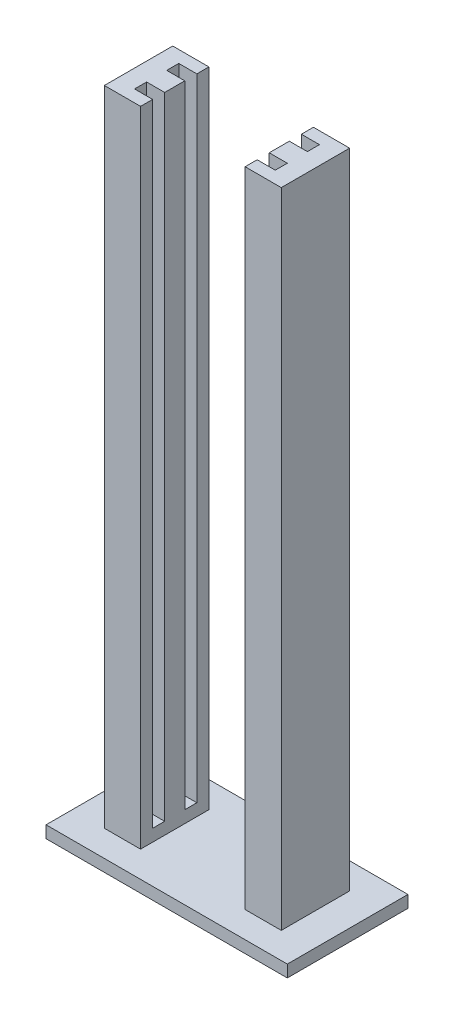
SolidWorks part; units mm, degrees
ref_plane "Front Plane" through (0, 0, 0) normal (0, 0, 1) x (1, 0, 0)
ref_plane "Top Plane" through (0, 0, 0) normal (0, 1, 0) x (1, 0, 0)
ref_plane "Right Plane" through (0, 0, 0) normal (1, 0, 0) x (0, 0, -1)
sketch "Sketch1" plane through (0, 0, 0) normal (0, 1, 0) x (1, 0, 0)
  line L1 (30, 15) -> (-30, 15)
  line L2 (30, 15) -> (30, -15)
  line L3 (30, -15) -> (-30, -15)
  line L4 (-30, 15) -> (-30, -15)
  line L5 (30, 15) -> (-30, -15) construction
  line L6 (30, -15) -> (-30, 15) construction
  point P0 (0, 0)
  dimension "D1" = 30
  dimension "D2" = 60
extrude "Boss-Extrude1" add sketch "Sketch1" along normal blind 3
sketch "Sketch2" plane through (0, 3, 0) normal (0, 1, 0) x (1, 0, 0)
  line L0 (0, 0) -> (-30, 0) construction
  line L1 (-30, 15) -> (-30, -15) construction
  line L2 (0, 0) -> (0, 15) construction
  line L3 (30, 15) -> (-30, 15) construction
  line L4 (13, -8.5) -> (22, -8.5)
  line L5 (-13, 8.5) -> (-22, 8.5)
  line L6 (-13, 8.5) -> (-13, -8.5)
  line L7 (-13, -8.5) -> (-22, -8.5)
  line L8 (-22, 8.5) -> (-22, -8.5)
  line L9 (-13, 8.5) -> (-22, -8.5) construction
  line L10 (-13, -8.5) -> (-22, 8.5) construction
  line L11 (22, 8.5) -> (22, -8.5)
  line L12 (13, 8.5) -> (22, 8.5)
  line L13 (13, 8.5) -> (13, -8.5)
  point P5 (-17.5, 0)
  dimension "D1" = 9
  dimension "D2" = 17
  dimension "D3" = 13
extrude "Boss-Extrude2" add sketch "Sketch2" along normal blind 160
sketch "Sketch3" plane through (0, 163, 0) normal (0, 1, 0) x (1, 0, 0)
  line L0 (-13, -8.5) -> (-13, 8.5) construction
  line L1 (-13, 5.5) -> (-17.5, 5.5)
  line L2 (-13, 5.5) -> (-13, 2.5)
  line L3 (-13, 2.5) -> (-17.5, 2.5)
  line L4 (-17.5, 5.5) -> (-17.5, 2.5)
  line L5 (-13, -8.5) -> (-13, 8.5) construction
  line L6 (-13, -2.5) -> (-17.5, -2.5)
  line L7 (-13, -2.5) -> (-13, -5.5)
  line L8 (-13, -5.5) -> (-17.5, -5.5)
  line L9 (-17.5, -2.5) -> (-17.5, -5.5)
  line L10 (0, 0) -> (0, 9.8393) construction
  line L11 (13, -5.5) -> (17.5, -5.5)
  line L12 (17.5, -2.5) -> (17.5, -5.5)
  line L13 (13, -2.5) -> (17.5, -2.5)
  line L14 (13, -2.5) -> (13, -5.5)
  line L15 (13, 2.5) -> (17.5, 2.5)
  line L16 (17.5, 5.5) -> (17.5, 2.5)
  line L17 (13, 5.5) -> (17.5, 5.5)
  line L18 (13, 5.5) -> (13, 2.5)
  line L19 (-13, 8.5) -> (-22, 8.5) construction
  line L21 (-22, -8.5) -> (-13, -8.5) construction
  dimension "D1" = 4.5
  dimension "D2" = 4.5
  dimension "D3" = 3
  dimension "D4" = 3
  dimension "D5" = 5
  dimension "D6" = 3
  dimension "D7" = 3
extrude "Cut-Extrude1" cut sketch "Sketch3" against normal blind 157
